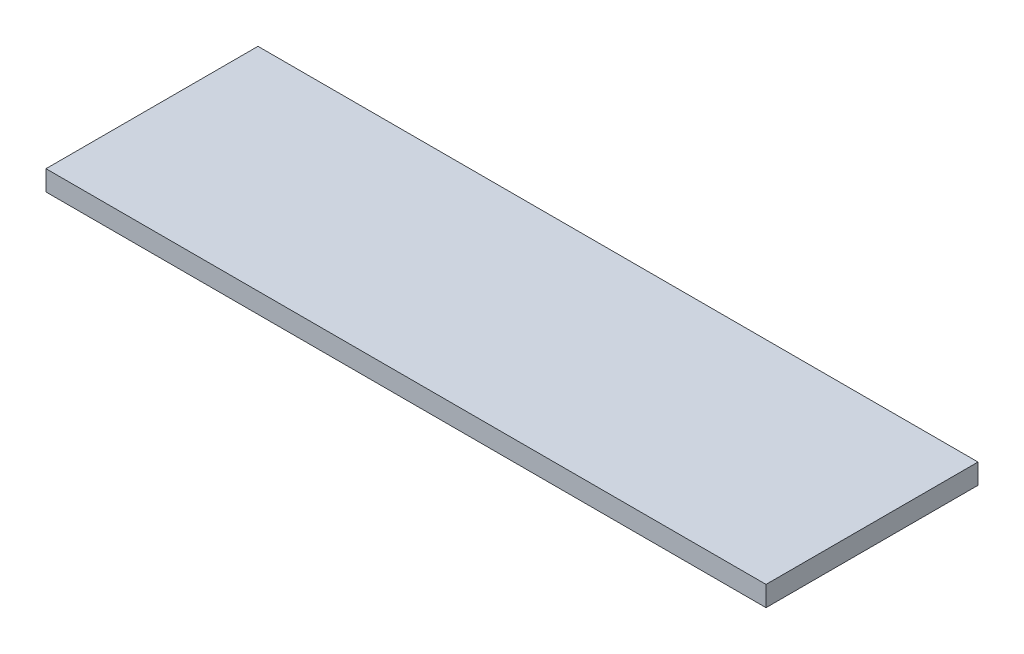
SolidWorks part; units mm, degrees
ref_plane "Спереди" through (0, 0, 0) normal (0, 0, 1) x (1, 0, 0)
ref_plane "Сверху" through (0, 0, 0) normal (0, 1, 0) x (1, 0, 0)
ref_plane "Справа" through (0, 0, 0) normal (1, 0, 0) x (0, 0, -1)
other "Configuration Table"
sketch "Эскиз1" plane through (0, 0, 0) normal (0, 1, 0) x (1, 0, 0)
  line L1 (0, -31.5) -> (107, -31.5)
  line L2 (0, -31.5) -> (0, 0)
  line L3 (0, 0) -> (107, 0)
  line L4 (107, -31.5) -> (107, 0)
extrude "Бобышка-Вытянуть1" add sketch "Эскиз1" along normal blind 3
